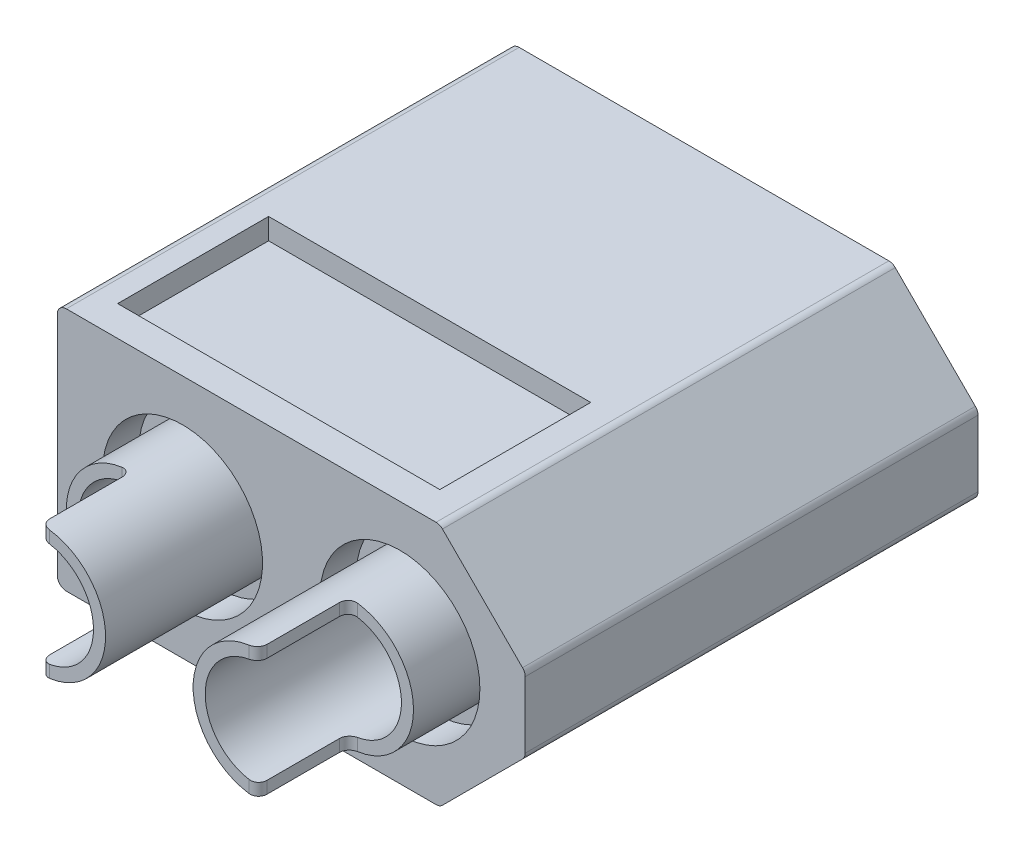
SolidWorks part; units mm, degrees
material "PVC 0.007 Plasticized"
ref_plane "Спереди" through (0, 0, 0) normal (0, 0, 1) x (1, 0, 0)
ref_plane "Сверху" through (0, 0, 0) normal (0, 1, 0) x (1, 0, 0)
ref_plane "Справа" through (0, 0, 0) normal (1, 0, 0) x (0, 0, -1)
sketch "Эскиз1" plane through (0, 0, 0) normal (0, 0, 1) x (1, 0, 0)
  line L0 (4.9216, 4.05) -> (7.75, 1.2216)
  line L1 (-7.75, 4.05) -> (7.75, 4.05)
  line L2 (-7.75, 4.05) -> (-7.75, -4.05)
  line L3 (-7.75, -4.05) -> (7.75, -4.05)
  line L4 (7.75, 4.05) -> (7.75, -4.05)
  line L5 (-7.75, 4.05) -> (7.75, -4.05) construction
  line L6 (-7.75, -4.05) -> (7.75, 4.05) construction
  line L7 (0, 0) -> (7.75, 0) construction
  line L8 (4.9216, -4.05) -> (7.75, -1.2216)
  point P0 (0, 0)
  dimension "D1" = 8.1
  dimension "D2" = 15.5
  dimension "D3" = 45
  dimension "D4" = 4
extrude "Бобышка-Вытянуть1" add sketch "Эскиз1" along normal blind 15 contours L3 L8 L4 L0 L1 L2
sketch "Эскиз2" plane through (0, 0, 0) normal (0, 0, -1) x (-1, 0, 0)
  line L12 (-4.6316, -3.35) -> (7.05, -3.35)
  line L13 (7.05, -3.35) -> (7.05, 3.35)
  line L14 (7.05, 3.35) -> (-4.6316, 3.35)
  line L15 (-4.6316, 3.35) -> (-7.05, 0.9316)
  line L16 (-7.05, 0.9316) -> (-7.05, -0.9316)
  line L17 (-7.05, -0.9316) -> (-4.6316, -3.35)
  line L18 (-4.6316, -3.35) -> (7.05, -3.35)
  line L19 (7.05, -3.35) -> (7.05, 3.35)
  line L20 (7.05, 3.35) -> (-4.6316, 3.35)
  line L21 (-4.6316, 3.35) -> (-7.05, 0.9316)
  line L22 (-7.05, 0.9316) -> (-7.05, -0.9316)
  line L23 (-7.05, -0.9316) -> (-4.6316, -3.35)
  dimension "D1" = 0.7
extrude "Вырез-Вытянуть1" cut sketch "Эскиз2" against normal blind 7.7
ref_plane "Плоскость1" through (0, 0, 1.5) normal (0, 0, -1) x (-1, 0, 0)
sketch "Эскиз3" plane through (0, 0, 1.5) normal (0, 0, -1) x (-1, 0, 0)
  line L1 (7.05, 3.35) -> (-4.6316, 3.35) construction
  line L2 (-0.75, 2.15) -> (0.75, 2.15)
  line L3 (-0.75, 2.15) -> (-0.75, 3.35)
  line L4 (-0.75, 3.35) -> (0.75, 3.35)
  line L5 (0.75, 2.15) -> (0.75, 3.35)
  line L6 (-0.75, 2.15) -> (0.75, 3.35) construction
  line L7 (-0.75, 3.35) -> (0.75, 2.15) construction
  point P1 (0, 2.75)
  dimension "D1" = 1.2
  dimension "D2" = 1.5
extrude "Бобышка-Вытянуть2" add sketch "Эскиз3" against normal up to surface (6.2 mm away) up to face at (1.5439, 0, 7.7)
sketch "Эскиз4" plane through (0, 0, 7.7) normal (0, 0, -1) x (-1, 0, 0)
  line L1 (0.75, 2.15) -> (-0.75, 2.15)
  line L2 (0.75, 2.15) -> (0.75, -1.85)
  line L3 (0.75, -1.85) -> (-0.75, -1.85)
  line L4 (-0.75, 2.15) -> (-0.75, -1.85)
  dimension "D1" = 4
  dimension "D2" = 1.5
extrude "Вырез-Вытянуть2" cut sketch "Эскиз4" against normal blind 1.2
sketch "Эскиз5" plane through (0, 0, 7.7) normal (0, 0, -1) x (-1, 0, 0)
  line L0 (0, 0) -> (0, -2.5029) construction
  circle A0 centre (3.6, 0) radius 2.15
  circle A1 centre (-3.6, 0) radius 2.15
  dimension "D1" = 4.3
  dimension "D2" = 7.2
extrude "Бобышка-Вытянуть3" add sketch "Эскиз5" along normal offset from surface 1.2 and the other way offset from surface (12 mm away) 4.7 up to face at (1.5439, 0, 0) other way up to face at (1.6405, 0, 15)
sketch "Эскиз6" plane through (0, 0, 15) normal (0, 0, 1) x (1, 0, 0)
  line L0 (0, 0) -> (0, -1.6207) construction
  circle A0 centre (3.6, 0) radius 2.15
  circle A1 centre (3.6, 0) radius 2.65
  circle A3 centre (3.6, 0) radius 2.15 construction
  circle A4 centre (-3.6, 0) radius 2.65
  circle A5 centre (-3.6, 0) radius 2.15
  dimension "D1" = 0.5
extrude "Вырез-Вытянуть3" cut sketch "Эскиз6" against normal blind 1.2
sketch "Эскиз7" plane through (0, 0, 19.7) normal (0, 0, 1) x (1, 0, 0)
  line L0 (0, 0) -> (0, 2.5309) construction
  circle A0 centre (-3.6, 0) radius 1.75
  circle A1 centre (-3.6, 0) radius 2.15 construction
  circle A2 centre (3.6, 0) radius 1.75
  dimension "D1" = 0.4
extrude "Вырез-Вытянуть4" cut sketch "Эскиз7" against normal blind 9
sketch "Эскиз8" plane through (0, 0, 0) normal (0, 1, 0) x (1, 0, 0)
  line L0 (0, 0) -> (0, -21.1053) construction
  line L1 (3.6, -19.7) -> (3.6, -16.7)
  line L2 (-5.75, -19.7) -> (-3.6, -19.7)
  line L3 (-5.75, -19.7) -> (-5.75, -16.7)
  line L4 (-5.75, -16.7) -> (-3.6, -16.7)
  line L5 (-3.6, -19.7) -> (-3.6, -16.7)
  line L6 (5.75, -16.7) -> (3.6, -16.7)
  line L7 (5.75, -19.7) -> (5.75, -16.7)
  line L8 (5.75, -19.7) -> (3.6, -19.7)
  dimension "D1" = 3
  dimension "D2" = 2.15
extrude "Вырез-Вытянуть5" cut sketch "Эскиз8" against normal through all both and the other way through all
sketch "Эскиз10" plane through (0, 0, 1.2) normal (0, 0, -1) x (-1, 0, 0)
  line L0 (0, 0) -> (0, -1.477) construction
  circle A0 centre (3.6, 0) radius 1.95
  circle A2 centre (3.6, 0) radius 2.15 construction
  circle A3 centre (3.6, 0) radius 2.15
  circle A5 centre (3.6, 0) radius 2.15 construction
  circle A6 centre (-3.6, 0) radius 2.15
  circle A7 centre (-3.6, 0) radius 1.95
  dimension "D1" = 0.2
extrude "Вырез-Вытянуть7" cut sketch "Эскиз10" against normal offset from surface (5.5 mm away) 1 up to face at (5.75, 0, 7.7)
sketch "Эскиз9" plane through (0, 0, 1.2) normal (0, 0, -1) x (-1, 0, 0)
  line L0 (0, 0) -> (0, -2.4191) construction
  line L1 (3.6, 2.5) -> (3.6, -2.5) construction
  line L2 (3.75, -2.5) -> (3.45, -2.5)
  line L3 (3.75, -2.5) -> (3.75, -0.7348)
  line L4 (3.75, 2.5) -> (3.45, 2.5)
  line L5 (3.45, -2.5) -> (3.45, -0.7348)
  line L6 (6.1, 0) -> (1.1, 0) construction
  line L7 (-3.75, -2.5) -> (-3.45, -2.5)
  line L8 (6.1, -0.15) -> (4.3348, -0.15)
  line L9 (6.1, -0.15) -> (6.1, 0.15)
  line L10 (6.1, 0.15) -> (4.3348, 0.15)
  line L11 (1.1, -0.15) -> (1.1, 0.15)
  line L12 (-3.45, -2.5) -> (-3.45, -0.7348)
  line L13 (-2.8652, -0.15) -> (-1.1, -0.15)
  line L14 (-1.1, -0.15) -> (-1.1, 0.15)
  line L15 (-2.8652, 0.15) -> (-1.1, 0.15)
  line L16 (-3.45, 0.7348) -> (-3.45, 2.5)
  line L17 (3.75, -0.009) -> (3.75, 0.009)
  line L18 (-3.75, 2.5) -> (-3.45, 2.5)
  line L19 (-3.75, 0.7348) -> (-3.75, 2.5)
  line L20 (-6.1, 0.15) -> (-4.3348, 0.15)
  line L21 (2.8652, -0.15) -> (1.1, -0.15)
  line L22 (-6.1, -0.15) -> (-6.1, 0.15)
  line L23 (-6.1, -0.15) -> (-4.3348, -0.15)
  line L24 (2.8652, 0.15) -> (1.1, 0.15)
  line L25 (3.45, 0.7348) -> (3.45, 2.5)
  line L26 (-3.75, -2.5) -> (-3.75, -0.7348)
  line L28 (3.75, 0.7348) -> (3.75, 2.5)
  arc A0 (3.45, 0.7348) -> (2.8652, 0.15) centre (3.6, 0) ccw
  arc A1 (2.8652, -0.15) -> (3.45, -0.7348) centre (3.6, 0) ccw
  arc A2 (3.75, -0.7348) -> (4.3348, -0.15) centre (3.6, 0) ccw
  arc A3 (4.3348, 0.15) -> (3.75, 0.7348) centre (3.6, 0) ccw
  arc A4 (-2.8652, -0.15) -> (-3.45, -0.7348) centre (-3.6, 0) cw
  arc A5 (-3.45, 0.7348) -> (-2.8652, 0.15) centre (-3.6, 0) cw
  arc A6 (-4.3348, 0.15) -> (-3.75, 0.7348) centre (-3.6, 0) cw
  arc A7 (-3.75, -0.7348) -> (-4.3348, -0.15) centre (-3.6, 0) cw
  dimension "D1" = 1.5
  dimension "D2" = 5
  dimension "D3" = 0.3
  dimension "D4" = 0.3
  dimension "D5" = 5
extrude "Вырез-Вытянуть6" cut sketch "Эскиз9" against normal offset from surface (6 mm away) 0.5
fillet "Скругление1" radius 1 8 edges at (4.9789, 1.3789, 1.2) (2.2211, 1.3789, 1.2) (4.9789, -1.3789, 1.2) (2.2211, -1.3789, 1.2) (-2.2211, -1.3789, 1.2) (-4.9789, -1.3789, 1.2) (-4.9789, 1.3789, 1.2) (-2.2211, 1.3789, 1.2)
fillet "Скругление2" radius 0.3 8 edges at (3.6, 1.95, 16.7) (3.6, -1.95, 16.7) (-3.6, -1.95, 16.7) (-3.6, 1.95, 16.7) (3.6, 1.95, 19.7) (3.6, -1.95, 19.7) (-3.6, -1.95, 19.7) (-3.6, 1.95, 19.7)
sketch "Эскиз11" plane through (0, 4.05, 0) normal (0, 1, 0) x (1, 0, 0)
  line L0 (-7.75, -15) -> (-7.75, 0) construction
  line L1 (-6.75, -14) -> (3.9216, -14)
  line L2 (-6.75, -14) -> (-6.75, -9)
  line L3 (-6.75, -9) -> (3.9216, -9)
  line L4 (3.9216, -14) -> (3.9216, -9)
  line L5 (-7.75, -15) -> (4.9216, -15) construction
  line L6 (4.9216, -15) -> (4.9216, 0) construction
  dimension "D1" = 1
  dimension "D2" = 1
  dimension "D3" = 1
  dimension "D4" = 5
extrude "Вырез-Вытянуть8" cut sketch "Эскиз11" against normal blind 0.7
mirror "Зеркальное отражение1" about plane through (0, 0, 0) normal (0, 1, 0) of "Вырез-Вытянуть8"
sketch "Эскиз12" plane through (0, -3.35, 0) normal (0, -1, 0) x (1, 0, 0)
  line L0 (2.4216, 12.5) -> (-5.4393, 12.5) construction
  line L1 (-6.75, 14) -> (3.9216, 14) construction
  line L2 (3.9216, 14) -> (3.9216, 9) construction
  text T0 "XT-60" font "Arial" height 2
  dimension "D1" = 1.5
  dimension "D2" = 1.5
extrude "Бобышка-Вытянуть4" add sketch "Эскиз12" along normal blind 0.2
fillet "Скругление3" radius 0.3 6 edges at (-7.75, 4.05, 7.5) (-7.75, -4.05, 7.5) (4.9216, 4.05, 7.5) (7.75, 1.2216, 7.5) (7.75, -1.2216, 7.5) (4.9216, -4.05, 7.5)
sketch "Sketch1" plane through (0, 0, 15) normal (0, 0, 1) x (1, 0, 0)
  point P0 (-3.6, 0)
  point P1 (3.6, 0)
ref_plane "Plane1" through (0, 0, 21.35) normal (0, 0, 1) x (1, 0, 0)
sketch "Sketch2" plane through (0, 0, 21.35) normal (0, 0, 1) x (1, 0, 0)
  point P0 (3.6, 0)
  point P1 (-3.6, 0)
